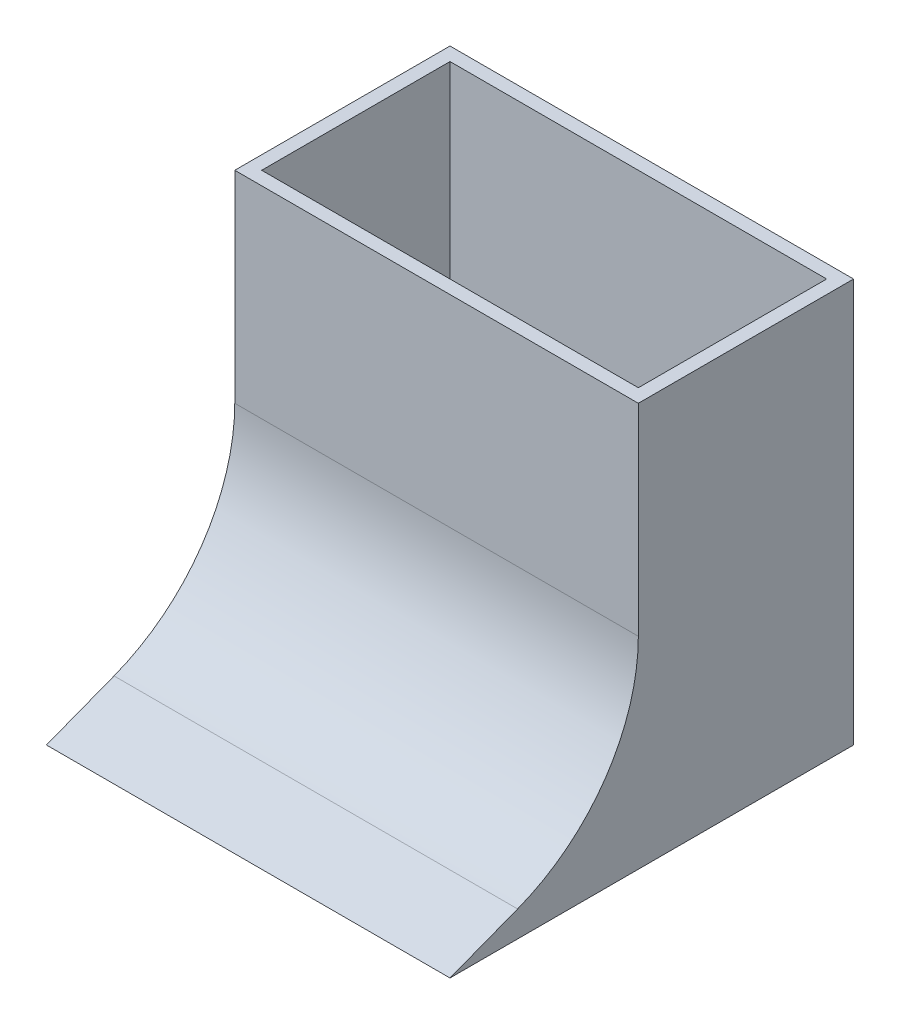
SolidWorks part; units mm, degrees
ref_plane "Plano frontal" through (0, 0, 0) normal (0, 0, 1) x (1, 0, 0)
ref_plane "Plano superior" through (0, 0, 0) normal (0, 1, 0) x (1, 0, 0)
ref_plane "Plano direito" through (0, 0, 0) normal (1, 0, 0) x (0, 0, -1)
sketch "Esboço1" plane through (0, 0, 0) normal (1, 0, 0) x (0, 0, -1)
  line L1 (42, -42) -> (-42, -42)
  line L2 (42, -42) -> (42, 42)
  line L3 (42, 42) -> (-42, 42)
  line L4 (-42, -42) -> (-42, 42)
  line L5 (42, -42) -> (-42, 42) construction
  line L6 (42, 42) -> (-42, -42) construction
  point P0 (0, 0)
  dimension "D1" = 84
  dimension "D2" = 84
extrude "Extrusão-Fina2" add sketch "Esboço1" along normal mid plane 90 thin thin type one direction wall 3
sketch "Esboço5" plane through (0, 0, 0) normal (1, 0, 0) x (0, 0, -1)
  line L0 (-45, 45) -> (-45, -45) construction
  line L1 (-42, -42) -> (-45, -42)
  line L2 (-42, -42) -> (-42, 42)
  line L3 (-42, 42) -> (-45, 42)
  line L4 (-45, -42) -> (-45, 42)
  line L5 (45, 45) -> (-45, 45) construction
  dimension "D1" = 3
extrude "Corte-extrusão1" cut sketch "Esboço5" against normal through all both and the other way through all
sketch "Esboço7" plane through (0, 0, 0) normal (1, 0, 0) x (0, 0, -1)
  line L0 (0, 0) -> (-45, 0) construction
  circle A0 centre (-45, 0) radius 42
  dimension "D1" = 45
extrude "Extrusão-Fina4" add sketch "Esboço7" along normal mid plane 90 thin
sketch "Esboço8" plane through (0, 0, 0) normal (1, 0, 0) x (0, 0, -1)
  line L0 (-45, -45) -> (-29.9216, -39.2)
  line L1 (-29.9216, -39.2) -> (-3, 0)
  line L2 (-3, 0) -> (-3, 45)
  line L3 (45, 45) -> (-45, 45) construction
  line L4 (-3, 45) -> (-95.3717, 45)
  line L5 (-95.3717, 45) -> (-95.3717, -45)
  line L6 (-95.3717, -45) -> (-45, -45)
  circle A0 centre (-45, 0) radius 42 construction
extrude "Corte-extrusão2" cut sketch "Esboço8" against normal through all both and the other way through all
sketch "Esboço9" plane through (0, 0, 0) normal (1, 0, 0) x (0, 0, -1)
  line L1 (-3, 45) -> (0, 45)
  line L2 (-3, 45) -> (-3, 0)
  line L3 (-3, 0) -> (0, 0)
  line L4 (0, 45) -> (0, 0)
extrude "Ressalto-extrusão1" add sketch "Esboço9" along normal mid plane 90
sketch "Esboço10" plane through (0, 0, 0) normal (0, 1, 0) x (1, 0, 0)
  line L0 (45, 45) -> (-45, 45) construction
  line L1 (-45, -45) -> (-42, -45)
  line L2 (-45, -45) -> (-45, 45)
  line L3 (-45, 45) -> (-42, 45)
  line L4 (-42, -45) -> (-42, 45)
  dimension "D1" = 3
extrude "Ressalto-extrusão2" add sketch "Esboço10" along normal mid plane 90
sketch "Esboço11" plane through (0, 0, 0) normal (0, 1, 0) x (1, 0, 0)
  line L0 (45, -45) -> (-42, -45) construction
  line L1 (45, 45) -> (42, 45)
  line L2 (45, 45) -> (45, -45)
  line L3 (45, -45) -> (42, -45)
  line L4 (42, 45) -> (42, -45)
  dimension "D1" = 3
extrude "Ressalto-extrusão3" add sketch "Esboço11" along normal mid plane 90
sketch "Esboço13" plane through (0, 0, 0) normal (1, 0, 0) x (0, 0, -1)
  line L0 (0, 0) -> (-3, 0) construction
  line L1 (-3, 0) -> (-3, 45)
  line L2 (45, 45) -> (-45, 45) construction
  line L3 (-3, 45) -> (-45, 45)
  line L4 (-45, 45) -> (-45, -45)
  line L5 (-45, -45) -> (-3, 0)
  dimension "D1" = 3
extrude "Corte-extrusão4" cut sketch "Esboço13" against normal through all both and the other way through all
sketch "Esboço14" plane through (0, 0, 0) normal (1, 0, 0) x (0, 0, -1)
  line L0 (0, 0) -> (-45, 0) construction
  circle A0 centre (-45, 0) radius 42
  dimension "D1" = 45
extrude "Corte-extrusão5" cut sketch "Esboço14" against normal through all both and the other way through all
sketch "Esboço15" plane through (0, 0, 0) normal (1, 0, 0) x (0, 0, -1)
  line L0 (-45, -45) -> (-29.9216, -39.2)
  line L1 (-29.9216, -39.2) -> (-45.5294, 1.376)
  line L3 (-45.5294, 1.376) -> (-45, -45)
extrude "Corte-extrusão6" cut sketch "Esboço15" against normal through all both and the other way through all
sketch "Esboço16" plane through (0, 0, 0) normal (0, 1, 0) x (1, 0, 0)
  line L0 (0, 0) -> (0, 21) construction
  line L1 (42, 42) -> (42, 0)
  line L2 (42, 42) -> (-42, 42)
  line L3 (42, 0) -> (-42, 0)
  line L4 (-42, 42) -> (-42, 0)
  line L5 (42, 42) -> (-42, 0) construction
  line L6 (42, 0) -> (-42, 42) construction
  line L8 (-45, 45) -> (-45, -3) construction
  line L10 (45, 45) -> (-45, 45) construction
  dimension "D1" = 21
  dimension "D2" = 3
  dimension "D3" = 3
extrude "Corte-extrusão8" cut sketch "Esboço16" along normal through all
